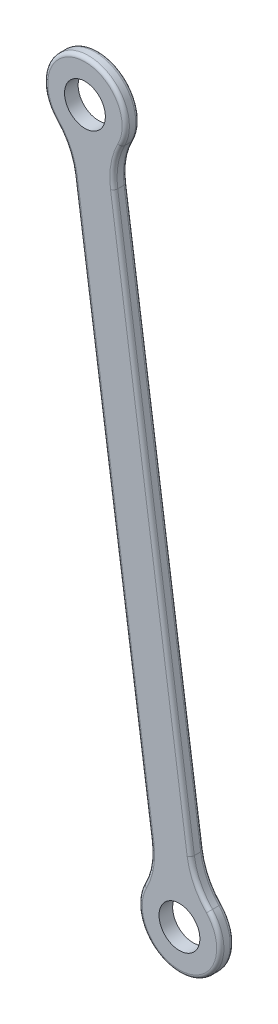
SolidWorks part; units mm, degrees
ref_plane "Front Plane" through (0, 0, 0) normal (0, 0, 1) x (1, 0, 0)
ref_plane "Top Plane" through (0, 0, 0) normal (0, 1, 0) x (1, 0, 0)
ref_plane "Right Plane" through (0, 0, 0) normal (1, 0, 0) x (0, 0, -1)
sketch "Sketch1" plane through (0, 0, 0) normal (0, 0, 1) x (1, 0, 0)
  line L0 (0, 0) -> (0, 28420.5788) construction
  line L1 (0, 0) -> (-28420.5788, 0) construction
  line L2 (-23, 10) -> (-28, 10)
  line L3 (-23, 0) -> (23, 0)
  line L4 (-23, 0) -> (-23, 10)
  line L5 (-23, 10) -> (23, 10)
  line L6 (23, 0) -> (23, 10)
  line L7 (-28, 10) -> (-41.8608, 50.4677)
  line L8 (-24.6313, 80.3256) -> (15.2446, 88.1625)
  line L9 (23, 10) -> (28, 10)
  line L10 (28, 10) -> (39.4051, 19.57)
  line L11 (39.4051, 19.57) -> (39.4051, 38.57)
  line L12 (39.4051, 38.57) -> (22.9346, 83.8223)
  line L13 (-20.22, 57.88) -> (-41.0516, 204.4066) construction
  line L14 (16.5541, 81.5) -> (-4.2776, 228.0266) construction
  line L15 (-75.8246, 230.8844) -> (-41.0516, 204.4066) construction
  line L16 (-41.0516, 204.4066) -> (-4.2776, 228.0266) construction
  line L17 (-4.2776, 228.0266) -> (-75.8246, 230.8844) construction
  line L18 (-75.8246, 230.8844) -> (-226.1828, 176.1814) construction
  line L19 (-204.7956, 140.0346) -> (9.2044, 224.1635) construction
  line L20 (-226.1828, 176.1814) -> (-204.7956, 140.0346) construction
  line L21 (-204.7956, 140.0346) -> (-256.0612, 159.9555) construction
  line L22 (-256.0612, 159.9555) -> (-226.1828, 176.1814) construction
  line L23 (-20.22, 57.88) -> (33.1708, 65.9687)
  line L24 (33.1708, 65.9687) -> (9.2044, 224.1635)
  circle A0 centre (-20.22, 57.88) radius 22.875 construction
  circle A1 centre (16.5541, 81.5) radius 6.79 construction
  arc A2 (-41.8608, 50.4677) -> (-24.6313, 80.3256) centre (-20.22, 57.88) cw
  arc A3 (15.2446, 88.1625) -> (22.9346, 83.8223) centre (16.5541, 81.5) cw
  circle A4 centre (-20.22, 57.88) radius 17.5 construction
  circle A5 centre (16.5541, 81.5) radius 7.5 construction
  circle A6 centre (-41.0516, 204.4066) radius 13.1881 construction
  circle A7 centre (-4.2776, 228.0266) radius 8.7345 construction
  circle A8 centre (-75.8246, 230.8844) radius 8.7345 construction
  circle A9 centre (-226.1828, 176.1814) radius 8.1525 construction
  circle A10 centre (-204.7956, 140.0346) radius 9.1166 construction
  dimension "D7" = 45.75
  dimension "D8" = 13.58
  dimension "D14" = 35
  dimension "D15" = 15
  dimension "D1" = 46
  dimension "D2" = 10
  dimension "D3" = 57.88
  dimension "D4" = 20.22
  dimension "D5" = 16.5541
  dimension "D6" = 81.5
  dimension "D9" = 5
  dimension "D10" = 5
  dimension "D11" = 140
  dimension "D12" = 19
  dimension "D13" = 160
  dimension "D16" = 148
  dimension "D17" = 110
  dimension "D18" = 160
  dimension "D19" = 54
  dimension "D20" = 214
  dimension "D21" = 42
  dimension "D22" = 34
  dimension "D23" = 55
  dimension "D24" = 54
  dimension "D25" = 160
sketch "Sketch3" plane through (0, 0, 0) normal (0, 0, 1) x (1, 0, 0)
  line L0 (33.1708, 65.9687) -> (9.2044, 224.1635) construction
  line L1 (33.1708, 65.9687) -> (9.2044, 224.1635)
  line L2 (9.2044, 224.1635) -> (33.1708, 65.9687) construction
  line L3 (13.6536, 224.8376) -> (37.62, 66.6427)
  line L4 (4.7551, 223.4895) -> (28.7215, 65.2946)
  arc A0 (14.8211, 217.1313) -> (5.9226, 215.7832) centre (9.2044, 224.1635) ccw
  arc A1 (27.554, 73.0009) -> (36.4525, 74.349) centre (33.1708, 65.9687) ccw
  arc A2 (13.6536, 224.8376) -> (4.7551, 223.4895) centre (9.2044, 224.1635) ccw
  arc A3 (28.7215, 65.2946) -> (37.62, 66.6427) centre (33.1708, 65.9687) ccw
  circle A4 centre (9.2044, 224.1635) radius 4.5
  circle A5 centre (33.1708, 65.9687) radius 4.5
  point P4 (21.1876, 145.0661)
  dimension "D1" = 18
  dimension "D2" = 18
  dimension "D3" = 9
sketch "Sketch2" plane through (0, 0, 0) normal (0, 0, 1) x (1, 0, 0)
  line L0 (16.5541, 81.5) -> (-4.2776, 228.0266) construction
  line L1 (15.9207, 85.9552) -> (-3.6442, 223.5714)
  line L2 (-4.2776, 228.0266) -> (16.5541, 81.5) construction
  line L3 (1.2747, 220.9434) -> (19.9122, 89.85)
  line L4 (-7.6357, 219.6766) -> (11.0018, 88.5832)
  arc A0 (1.2747, 220.9434) -> (-7.6357, 219.6766) centre (-4.2776, 228.0266) ccw
  arc A1 (11.0018, 88.5832) -> (19.9122, 89.85) centre (16.5541, 81.5) ccw
  arc A2 (0.1776, 228.66) -> (-8.7328, 227.3932) centre (-4.2776, 228.0266) ccw
  arc A3 (12.0989, 80.8666) -> (21.0093, 82.1334) centre (16.5541, 81.5) ccw
  circle A4 centre (-4.2776, 228.0266) radius 4.5
  circle A5 centre (16.5541, 81.5) radius 4.5
  point P4 (6.1383, 154.7633)
  dimension "D1" = 18
  dimension "D2" = 18
  dimension "D3" = 9
extrude "Boss-Extrude1" add sketch "Sketch2" along normal mid plane 3
fillet "Fillet2" radius 15 4 edges at (1.2747, 220.9434, 0) (19.9122, 89.85, 0) (11.0018, 88.5832, 0) (-7.6357, 219.6766, 0)
fillet "Fillet1" radius 0.8 16 edges at (-5.5443, 236.937, 1.5) (10.5935, 155.3967, 1.5) (17.8208, 72.5896, 1.5) (1.6831, 154.1299, 1.5) (-5.5443, 236.937, -1.5) (1.6831, 154.1299, -1.5) (17.8208, 72.5896, -1.5) (10.5935, 155.3967, -1.5) (2.2137, 219.4567, -1.5) (-8.1232, 217.9871, -1.5) (10.0628, 90.0699, -1.5) (20.3997, 91.5395, -1.5) (2.2137, 219.4567, 1.5) (20.3997, 91.5395, 1.5) (10.0628, 90.0699, 1.5) (-8.1232, 217.9871, 1.5)
